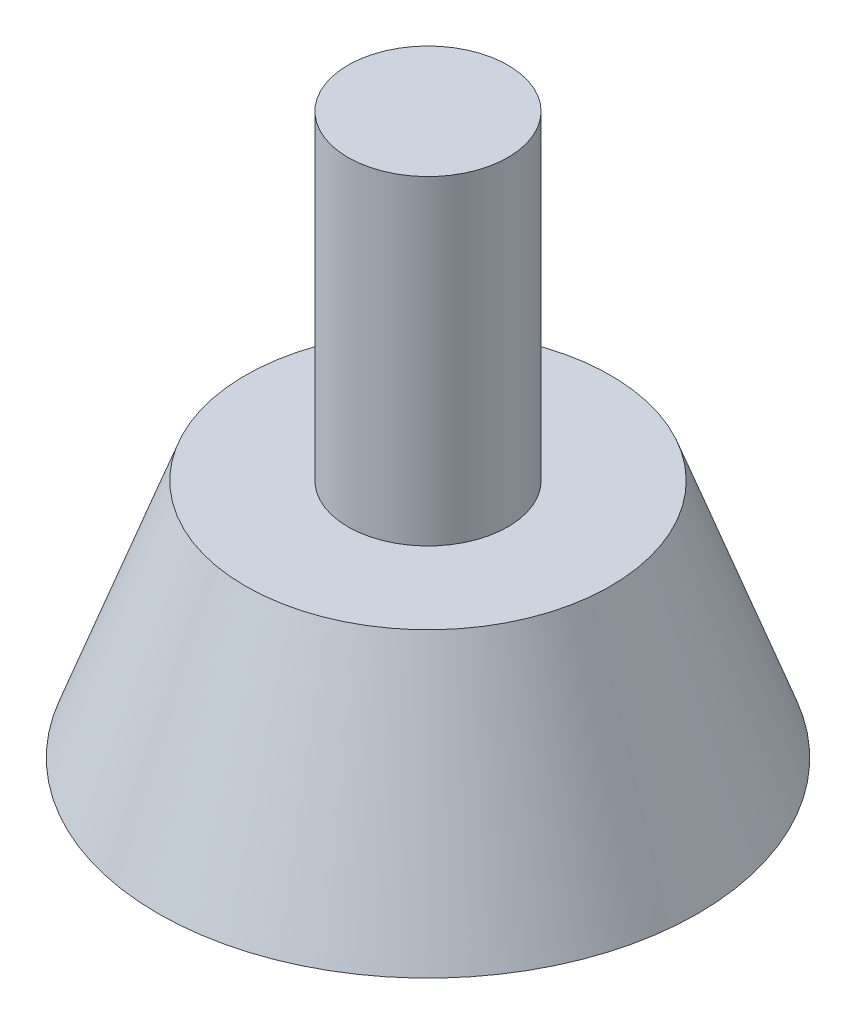
SolidWorks part; units mm, degrees
ref_plane "Front Plane" through (0, 0, 0) normal (0, 0, 1) x (1, 0, 0)
ref_plane "Top Plane" through (0, 0, 0) normal (0, 1, 0) x (1, 0, 0)
ref_plane "Right Plane" through (0, 0, 0) normal (1, 0, 0) x (0, 0, -1)
sketch "Sketch2" plane through (0, 0, 0) normal (0, 1, 0) x (1, 0, 0)
  circle A0 centre (0, 0) radius 13.5
  dimension "D1" = 27
extrude "Boss-Extrude1" add sketch "Sketch2" along normal blind 12 draft 20
sketch "Sketch3" plane through (0, 12, 0) normal (0, 1, 0) x (1, 0, 0)
  circle A0 centre (0, 0) radius 4
  dimension "D1" = 8
extrude "Boss-Extrude2" add sketch "Sketch3" along normal blind 16
